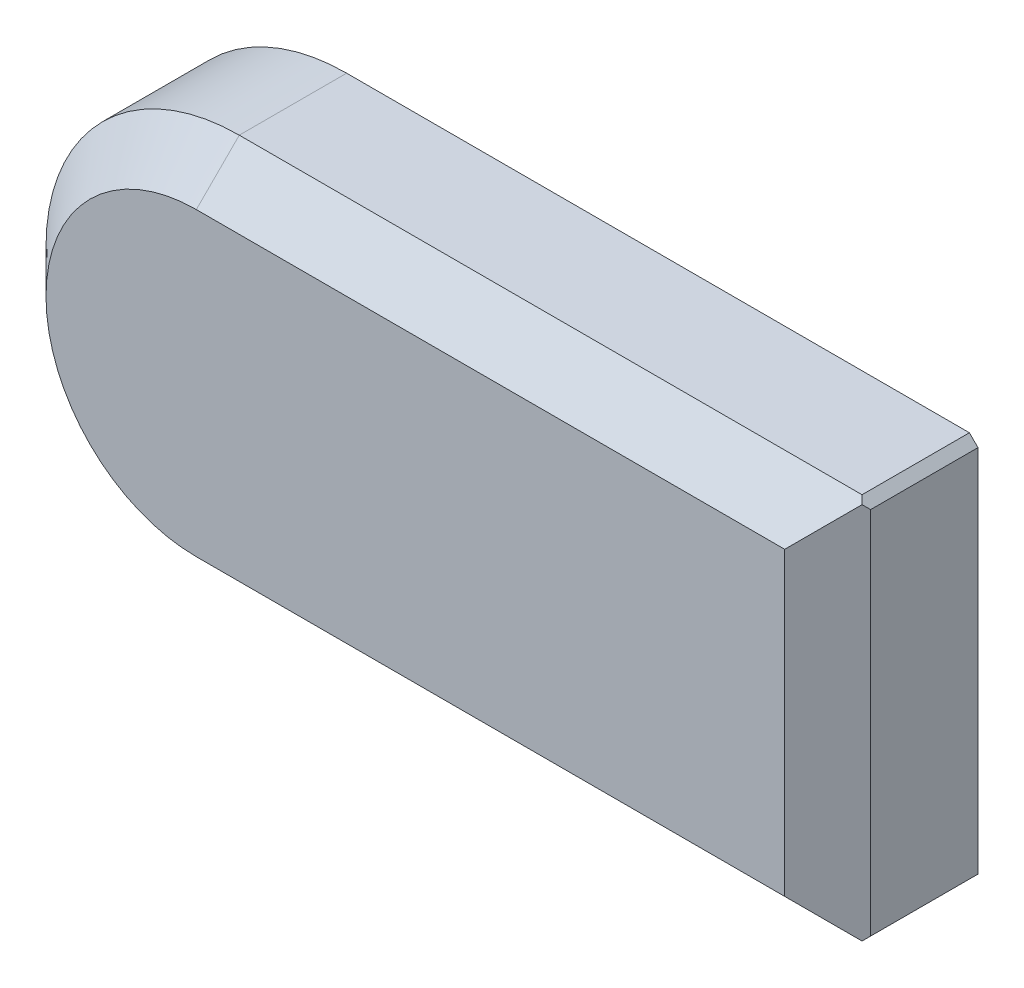
SolidWorks part; units mm, degrees
ref_plane "前视基准面" through (0, 0, 0) normal (0, 0, 1) x (1, 0, 0)
ref_plane "上视基准面" through (0, 0, 0) normal (0, 1, 0) x (1, 0, 0)
ref_plane "右视基准面" through (0, 0, 0) normal (1, 0, 0) x (0, 0, -1)
other "Configuration Table"
sketch "草图1" plane through (0, 0, 0) normal (0, 0, 1) x (1, 0, 0)
  line L1 (-36.75, 22.5) -> (36.75, 22.5)
  line L2 (-36.75, 22.5) -> (-36.75, -22.5)
  line L3 (-36.75, -22.5) -> (36.75, -22.5)
  line L4 (36.75, 22.5) -> (36.75, -22.5)
  line L5 (-36.75, 22.5) -> (36.75, -22.5) construction
  line L6 (-36.75, -22.5) -> (36.75, 22.5) construction
  circle A0 centre (-36.75, 0) radius 22.5
  point P0 (0, 0)
  dimension "D1" = 73.5
  dimension "D2" = 45
extrude "凸台-拉伸1" add sketch "草图1" along normal blind 17.5 contours L2 A0 | L2 A0 | A0 L3 L4 L1
chamfer "倒角1" distance 5 angle 45 4 edges at (0, -22.5, 17.5) (-59.25, 0, 17.5) (0, 22.5, 17.5) (36.75, 0, 17.5)
shell "抽壳1" thickness 2.5
sketch "草图2" plane through (0, 0, 0) normal (0, 0, -1) x (-1, 0, 0)
  line L0 (36.75, -20) -> (-34.25, -20) construction
  line L1 (36.75, 20) -> (-34.25, 20) construction
  line L2 (-34.25, 20) -> (-34.25, -20) construction
  line L3 (36.75, -20) -> (-34.25, -20)
  line L4 (36.75, 20) -> (-34.25, 20)
  line L5 (-34.25, 20) -> (-34.25, -20)
  line L6 (36.75, 21.2) -> (-35.45, 21.2)
  line L7 (-35.45, 21.2) -> (-35.45, -21.2)
  line L8 (36.75, -21.2) -> (-35.45, -21.2)
  arc A0 (36.75, -20) -> (36.75, 20) centre (36.75, 0) ccw construction
  arc A1 (36.75, -20) -> (36.75, 20) centre (36.75, 0) ccw
  arc A2 (36.75, -21.2) -> (36.75, 21.2) centre (36.75, 0) ccw
  dimension "D1" = 1.2
extrude "切除-拉伸1" cut sketch "草图2" against normal blind 1.2
sketch "草图3" plane through (0, 0, 15) normal (0, 0, -1) x (-1, 0, 0)
  line L0 (-36.75, 0) -> (11.25, 0) construction
  line L1 (-36.75, 22.5) -> (-36.75, -22.5) construction
  circle A0 centre (11.25, 0) radius 5
  dimension "D2" = 10
  dimension "D1" = 48
extrude "凸台-拉伸2" add sketch "草图3" along normal offset from surface (14 mm away) 1 up to face at (-5.95, 0, 0)
sketch "草图4" plane through (0, 0, 1) normal (0, 0, -1) x (-1, 0, 0)
  line L1 (9.6623, -2.75) -> (12.8377, -2.75)
  line L2 (12.8377, -2.75) -> (14.4254, 0)
  line L3 (14.4254, 0) -> (12.8377, 2.75)
  line L4 (12.8377, 2.75) -> (9.6623, 2.75)
  line L5 (9.6623, 2.75) -> (8.0746, 0)
  line L6 (8.0746, 0) -> (9.6623, -2.75)
  circle A0 centre (11.25, 0) radius 2.75 construction
  dimension "D1" = 5.5
extrude "切除-拉伸2" cut sketch "草图4" against normal blind 2.4
sketch "草图5" plane through (0, 0, 3.4) normal (0, 0, -1) x (-1, 0, 0)
  circle A0 centre (11.25, 0) radius 1.6
  dimension "D1" = 3.2
extrude "切除-拉伸3" cut sketch "草图5" against normal blind 6
chamfer "倒角2" distance 1 angle 45 2 edges at (36.75, 22.5, 6.25) (36.75, -22.5, 6.25)
